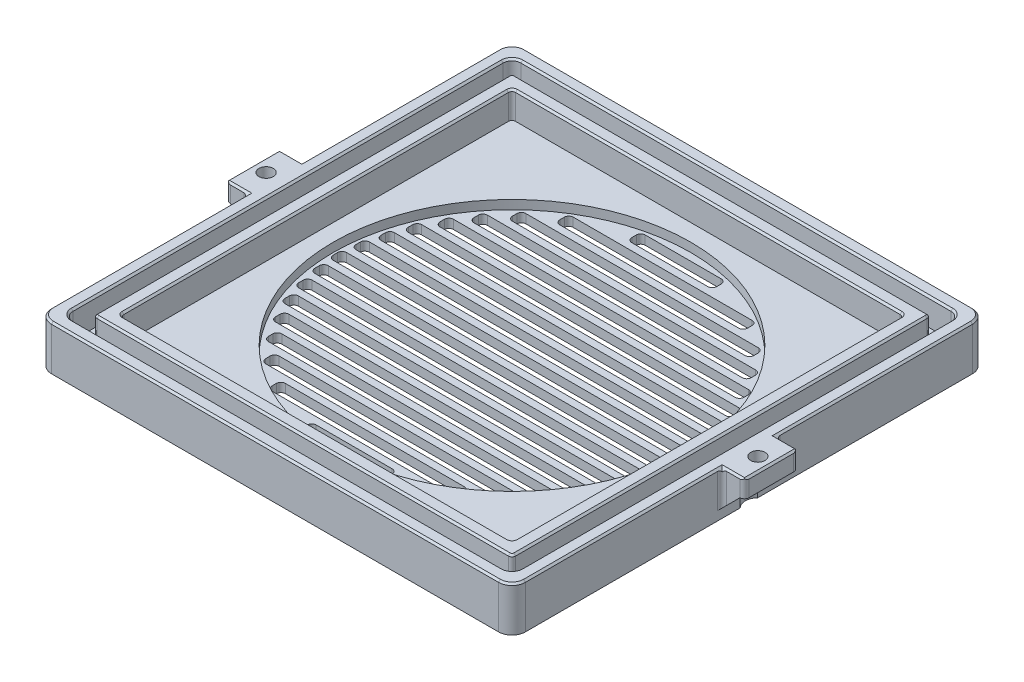
SolidWorks part; units mm, degrees
ref_plane "前视基准面" through (0, 0, 0) normal (0, 0, 1) x (1, 0, 0)
ref_plane "上视基准面" through (0, 0, 0) normal (0, 1, 0) x (1, 0, 0)
ref_plane "右视基准面" through (0, 0, 0) normal (1, 0, 0) x (0, 0, -1)
other "Configuration Table"
sketch "草图1" plane through (0, 0, 0) normal (0, 1, 0) x (1, 0, 0)
  line L1 (0, 0) -> (106, 0)
  line L2 (0, 0) -> (0, 106)
  line L3 (0, 106) -> (106, 106)
  line L4 (106, 0) -> (106, 106)
  dimension "D1" = 106
  dimension "D2" = 106
extrude "凸台-拉伸1" add sketch "草图1" along normal blind 10
sketch "草图2" plane through (0, 10, 0) normal (0, 1, 0) x (1, 0, 0)
  line L8 (2.9, 103.1) -> (2.9, 2.9)
  line L9 (2.9, 2.9) -> (103.1, 2.9)
  line L10 (103.1, 2.9) -> (103.1, 103.1)
  line L11 (103.1, 103.1) -> (2.9, 103.1)
  line L12 (2.9, 103.1) -> (2.9, 2.9)
  line L13 (2.9, 2.9) -> (103.1, 2.9)
  line L14 (103.1, 2.9) -> (103.1, 103.1)
  line L15 (103.1, 103.1) -> (2.9, 103.1)
  line L20 (6.2, 99.8) -> (6.2, 6.2)
  line L21 (6.2, 6.2) -> (99.8, 6.2)
  line L22 (99.8, 6.2) -> (99.8, 99.8)
  line L23 (99.8, 99.8) -> (6.2, 99.8)
  line L24 (6.2, 99.8) -> (6.2, 6.2)
  line L25 (6.2, 6.2) -> (99.8, 6.2)
  line L26 (99.8, 6.2) -> (99.8, 99.8)
  line L27 (99.8, 99.8) -> (6.2, 99.8)
  dimension "D1" = 2.9
  dimension "D2" = 6.2
extrude "切除-拉伸1" cut sketch "草图2" against normal blind 6
sketch "草图3" plane through (0, 10, 0) normal (0, 1, 0) x (1, 0, 0)
  line L8 (96.8, 96.8) -> (9.2, 96.8)
  line L9 (9.2, 96.8) -> (9.2, 9.2)
  line L10 (9.2, 9.2) -> (96.8, 9.2)
  line L11 (96.8, 9.2) -> (96.8, 96.8)
  line L12 (96.8, 96.8) -> (9.2, 96.8)
  line L13 (9.2, 96.8) -> (9.2, 9.2)
  line L14 (9.2, 9.2) -> (96.8, 9.2)
  line L15 (96.8, 9.2) -> (96.8, 96.8)
  dimension "D1" = 3
extrude "切除-拉伸3" cut sketch "草图3" against normal blind 6
sketch "草图4" plane through (0, 4, 0) normal (0, -1, 0) x (-1, 0, 0)
  line L0 (0, 0) -> (-106, 0) construction
  line L1 (0, 106) -> (0, 0) construction
  circle A0 centre (-53, 53) radius 40
  point P4 (-53, 0)
  point P7 (0, 53)
  dimension "D3" = 80
  dimension "D1" = 0
  dimension "D2" = 0
extrude "切除-拉伸4" cut sketch "草图4" along normal blind 2
fillet "圆角1" radius 2 4 edges at (103.1, 7, -103.1) (2.9, 7, -103.1) (2.9, 7, -2.9) (103.1, 7, -2.9)
fillet "圆角2" radius 3 4 edges at (106, 5, -106) (0, 5, -106) (0, 5, 0) (106, 5, 0)
fillet "圆角3" radius 0.8 8 edges at (99.8, 7, -99.8) (6.2, 7, -99.8) (6.2, 7, -6.2) (99.8, 7, -6.2) (9.2, 7, -9.2) (9.2, 7, -96.8) (96.8, 7, -96.8) (96.8, 7, -9.2)
sketch "草图6" plane through (0, 10, 0) normal (0, 1, 0) x (1, 0, 0)
  line L0 (0, 103) -> (0, 3) construction
  line L1 (0, 47) -> (-5, 47)
  line L2 (0, 47) -> (0, 59)
  line L3 (0, 59) -> (-5, 59)
  line L4 (-5, 47) -> (-5, 59)
  line L5 (106, 3) -> (106, 103) construction
  line L6 (106, 59) -> (111, 59)
  line L7 (106, 59) -> (106, 47)
  line L8 (106, 47) -> (111, 47)
  line L9 (111, 59) -> (111, 47)
  point P6 (0, 53)
  point P7 (0, 53)
  point P14 (106, 53)
  point P15 (106, 53)
  dimension "D1" = 0
  dimension "D2" = 5
  dimension "D3" = 12
  dimension "D4" = 0
  dimension "D5" = 12
  dimension "D6" = 5
extrude "凸台-拉伸3" add sketch "草图6" against normal blind 4
chamfer "倒角1" distance 0.4 angle 45 40 edges at (105.1213, 10, -0.8787) (53, 10, 0) (0.8787, 10, -0.8787) (0, 10, -25) (0, 10, -81) (0.8787, 10, -105.1213) (53, 10, -106) (105.1213, 10, -105.1213) (106, 10, -81) (106, 10, -25) (3.4858, 10, -3.4858) (53, 10, -2.9) (102.5142, 10, -3.4858) (103.1, 10, -53) (102.5142, 10, -102.5142) (53, 10, -103.1) (3.4858, 10, -102.5142) (2.9, 10, -53) (99.5657, 10, -6.4343) (53, 10, -6.2) (6.4343, 10, -6.4343) (6.2, 10, -53) (6.4343, 10, -99.5657) (53, 10, -99.8) (99.5657, 10, -99.5657) (99.8, 10, -53) (9.4343, 10, -96.5657) (9.2, 10, -53) (9.4343, 10, -9.4343) (53, 10, -9.2) (96.5657, 10, -9.4343) (96.8, 10, -53) (96.5657, 10, -96.5657) (53, 10, -96.8) (-2.5, 10, -47) (-5, 10, -53) (-2.5, 10, -59) (108.5, 10, -59) (111, 10, -53) (108.5, 10, -47)
chamfer "倒角2" distance 4 angle 45 2 edges at (106, 6, -53) (0, 6, -53)
sketch "草图7" plane through (0, 6, 0) normal (0, -1, 0) x (-1, 0, 0)
  line L0 (-111, 47) -> (-111, 59) construction
  line L1 (5, 59) -> (5, 47) construction
  circle A0 centre (2, 53) radius 1.6
  circle A1 centre (-108, 53) radius 1.6
  dimension "D1" = 3.2
  dimension "D2" = 3.2
  dimension "D3" = 3
  dimension "D4" = 3
extrude "切除-拉伸6" cut sketch "草图7" against normal blind 4 and the other way through all
sketch "草图8" plane through (0, 6, 0) normal (0, -1, 0) x (-1, 0, 0)
  circle A0 centre (2, 53) radius 2.8
  circle A1 centre (-108, 53) radius 2.8
  dimension "D1" = 5.6
  dimension "D2" = 5.6
extrude "切除-拉伸7" cut sketch "草图8" along normal through all
fillet "圆角4" radius 1 8 edges at (106, 5.8, -47) (106, 5.8, -59) (111, 7.8, -59) (111, 7.8, -47) (0, 5.8, -47) (0, 5.8, -59) (-5, 7.8, -47) (-5, 7.8, -59)
sketch "草图9" plane through (0, 2, 0) normal (0, 1, 0) x (1, 0, 0)
  line L0 (13.5, 53) -> (71.3783, 53) construction
  line L1 (13.5, 54.5) -> (92.5, 54.5)
  line L2 (13.5, 54.5) -> (13.5, 51.5)
  line L3 (13.5, 51.5) -> (92.5, 51.5)
  line L4 (92.5, 54.5) -> (92.5, 51.5)
  line L5 (14, 59.1) -> (92, 59.1)
  line L6 (14, 59.1) -> (14, 56.1)
  line L7 (14, 56.1) -> (92, 56.1)
  line L8 (92, 59.1) -> (92, 56.1)
  line L9 (15, 60.7) -> (91, 60.7)
  line L10 (15, 60.7) -> (15, 63.7)
  line L11 (15, 63.7) -> (91, 63.7)
  line L12 (91, 60.7) -> (91, 63.7)
  line L13 (16.5, 68.3) -> (89.5, 68.3)
  line L14 (16.5, 68.3) -> (16.5, 65.3)
  line L15 (16.5, 65.3) -> (89.5, 65.3)
  line L16 (89.5, 68.3) -> (89.5, 65.3)
  line L17 (19, 72.9) -> (87, 72.9)
  line L18 (19, 72.9) -> (19, 69.9)
  line L19 (19, 69.9) -> (87, 69.9)
  line L20 (87, 72.9) -> (87, 69.9)
  line L21 (22, 77.5) -> (84, 77.5)
  line L22 (22, 77.5) -> (22, 74.5)
  line L23 (22, 74.5) -> (84, 74.5)
  line L24 (84, 77.5) -> (84, 74.5)
  line L25 (26, 82.1) -> (80, 82.1)
  line L26 (26, 82.1) -> (26, 79.1)
  line L27 (26, 79.1) -> (80, 79.1)
  line L28 (80, 82.1) -> (80, 79.1)
  line L29 (32, 86.7) -> (74, 86.7)
  line L30 (32, 86.7) -> (32, 83.7)
  line L31 (32, 83.7) -> (74, 83.7)
  line L32 (74, 86.7) -> (74, 83.7)
  line L33 (43.5, 91.3) -> (62.5, 91.3)
  line L34 (43.5, 91.3) -> (43.5, 88.3)
  line L35 (43.5, 88.3) -> (62.5, 88.3)
  line L36 (62.5, 91.3) -> (62.5, 88.3)
  line L37 (43.5, 17.7) -> (62.5, 17.7)
  line L38 (62.5, 14.7) -> (62.5, 17.7)
  line L39 (43.5, 14.7) -> (62.5, 14.7)
  line L40 (43.5, 14.7) -> (43.5, 17.7)
  line L41 (32, 22.3) -> (74, 22.3)
  line L42 (74, 19.3) -> (74, 22.3)
  line L43 (32, 19.3) -> (74, 19.3)
  line L44 (32, 19.3) -> (32, 22.3)
  line L45 (26, 26.9) -> (80, 26.9)
  line L46 (80, 23.9) -> (80, 26.9)
  line L47 (26, 23.9) -> (80, 23.9)
  line L48 (26, 23.9) -> (26, 26.9)
  line L49 (22, 31.5) -> (84, 31.5)
  line L50 (84, 28.5) -> (84, 31.5)
  line L51 (22, 28.5) -> (84, 28.5)
  line L52 (22, 28.5) -> (22, 31.5)
  line L53 (19, 36.1) -> (87, 36.1)
  line L54 (87, 33.1) -> (87, 36.1)
  line L55 (19, 33.1) -> (87, 33.1)
  line L56 (19, 33.1) -> (19, 36.1)
  line L57 (16.5, 40.7) -> (89.5, 40.7)
  line L58 (89.5, 37.7) -> (89.5, 40.7)
  line L59 (16.5, 37.7) -> (89.5, 37.7)
  line L60 (16.5, 37.7) -> (16.5, 40.7)
  line L61 (15, 42.3) -> (91, 42.3)
  line L62 (91, 45.3) -> (91, 42.3)
  line L63 (15, 45.3) -> (91, 45.3)
  line L64 (15, 45.3) -> (15, 42.3)
  line L65 (14, 49.9) -> (92, 49.9)
  line L66 (92, 46.9) -> (92, 49.9)
  line L67 (14, 46.9) -> (92, 46.9)
  line L68 (14, 46.9) -> (14, 49.9)
  circle A0 centre (53, 53) radius 40 construction
  circle A1 centre (53, 53) radius 40 construction
  point P4 (53, 51.5)
  point P7 (13.5, 53)
  point P14 (53, 56.1)
  point P15 (53, 54.5)
  point P20 (53, 60.7)
  point P21 (53, 59.1)
  point P26 (53, 68.3)
  point P27 (53, 63.7)
  point P32 (53, 69.9)
  point P37 (53, 77.5)
  point P38 (53, 72.9)
  point P43 (53, 82.1)
  point P48 (53, 86.7)
  point P53 (53, 91.3)
  dimension "D1" = 0
  dimension "D2" = 3
  dimension "D3" = 0
  dimension "D4" = 79
  dimension "D5" = 3
  dimension "D6" = 0
  dimension "D7" = 1.6
  dimension "D8" = 78
  dimension "D9" = 3
  dimension "D10" = 0
  dimension "D11" = 1.6
  dimension "D12" = 76
  dimension "D13" = 3
  dimension "D14" = 1.6
  dimension "D15" = 0
  dimension "D16" = 73
  dimension "D17" = 3
  dimension "D18" = 1.6
  dimension "D19" = 0
  dimension "D20" = 68
  dimension "D21" = 3
  dimension "D22" = 1.6
  dimension "D23" = 0
  dimension "D24" = 62
  dimension "D25" = 3
  dimension "D26" = 1.6
  dimension "D27" = 0
  dimension "D28" = 54
  dimension "D29" = 3
  dimension "D30" = 1.6
  dimension "D31" = 0
  dimension "D32" = 42
  dimension "D33" = 1.6
  dimension "D34" = 3
  dimension "D35" = 0
  dimension "D36" = 19
extrude "切除-拉伸8" cut sketch "草图9" against normal blind 10
fillet "圆角5" radius 1 68 edges at (43.5, 1, -91.3) (62.5, 1, -91.3) (62.5, 1, -88.3) (43.5, 1, -88.3) (32, 1, -86.7) (74, 1, -86.7) (74, 1, -83.7) (32, 1, -83.7) (26, 1, -82.1) (80, 1, -82.1) (80, 1, -79.1) (26, 1, -79.1) (22, 1, -77.5) (84, 1, -77.5) (84, 1, -74.5) (22, 1, -74.5) (19, 1, -72.9) (87, 1, -72.9) (87, 1, -69.9) (19, 1, -69.9) (16.5, 1, -68.3) (89.5, 1, -68.3) (89.5, 1, -65.3) (16.5, 1, -65.3) (15, 1, -63.7) (91, 1, -63.7) (91, 1, -60.7) (15, 1, -60.7) (92, 1, -59.1) (92, 1, -56.1) (14, 1, -56.1) (92.5, 1, -54.5) (92.5, 1, -51.5) (13.5, 1, -51.5) (14, 1, -59.1) (13.5, 1, -54.5) (43.5, 1, -17.7) (62.5, 1, -17.7) (62.5, 1, -14.7) (43.5, 1, -14.7) (32, 1, -22.3) (74, 1, -22.3) (74, 1, -19.3) (32, 1, -19.3) (26, 1, -26.9) (80, 1, -26.9) (80, 1, -23.9) (26, 1, -23.9) (22, 1, -31.5) (84, 1, -31.5) (84, 1, -28.5) (22, 1, -28.5) (19, 1, -36.1) (87, 1, -36.1) (87, 1, -33.1) (19, 1, -33.1) (16.5, 1, -40.7) (89.5, 1, -40.7) (89.5, 1, -37.7) (16.5, 1, -37.7) (15, 1, -45.3) (91, 1, -45.3) (91, 1, -42.3) (15, 1, -42.3) (14, 1, -49.9) (92, 1, -49.9) (92, 1, -46.9) (14, 1, -46.9)
